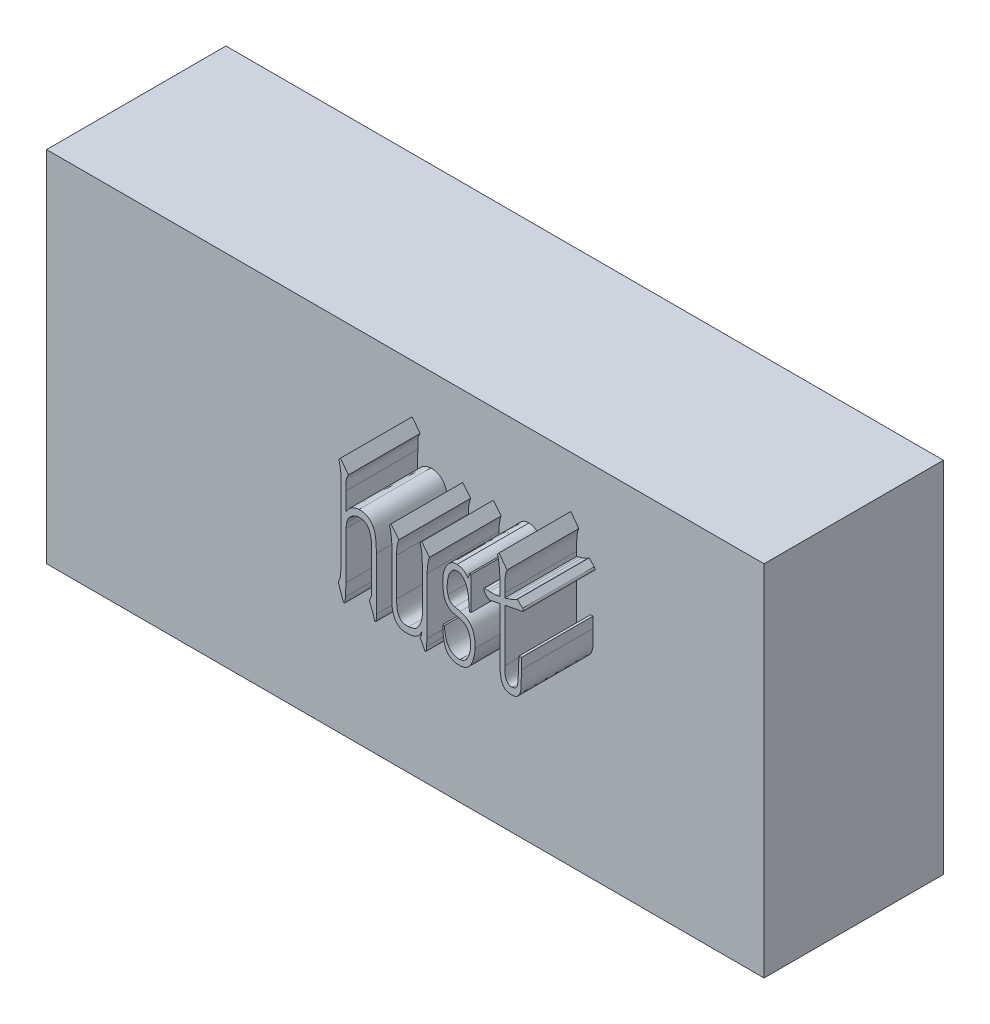
SolidWorks part; units mm, degrees
ref_plane "前视基准面" through (0, 0, 0) normal (0, 0, 1) x (1, 0, 0)
ref_plane "上视基准面" through (0, 0, 0) normal (0, 1, 0) x (1, 0, 0)
ref_plane "右视基准面" through (0, 0, 0) normal (1, 0, 0) x (0, 0, -1)
other "Configuration Table"
sketch "草图1" plane through (0, 0, 0) normal (0, 0, 1) x (1, 0, 0)
  line L1 (-10, -5) -> (10, -5)
  line L2 (-10, -5) -> (-10, 5)
  line L3 (-10, 5) -> (10, 5)
  line L4 (10, -5) -> (10, 5)
  line L5 (-10, -5) -> (10, 5) construction
  line L6 (-10, 5) -> (10, -5) construction
  point P0 (0, 0)
extrude "凸台-拉伸1" add sketch "草图1" along normal blind 5
sketch "草图2" plane through (0, 0, 5) normal (0, 0, 1) x (1, 0, 0)
  line L0 (-3.6, 0) -> (3.6, 0) construction
  text T0 "hust" font "汉仪长仿宋体" height 3.5
extrude "凸台-拉伸2" add sketch "草图2" along normal blind 2
